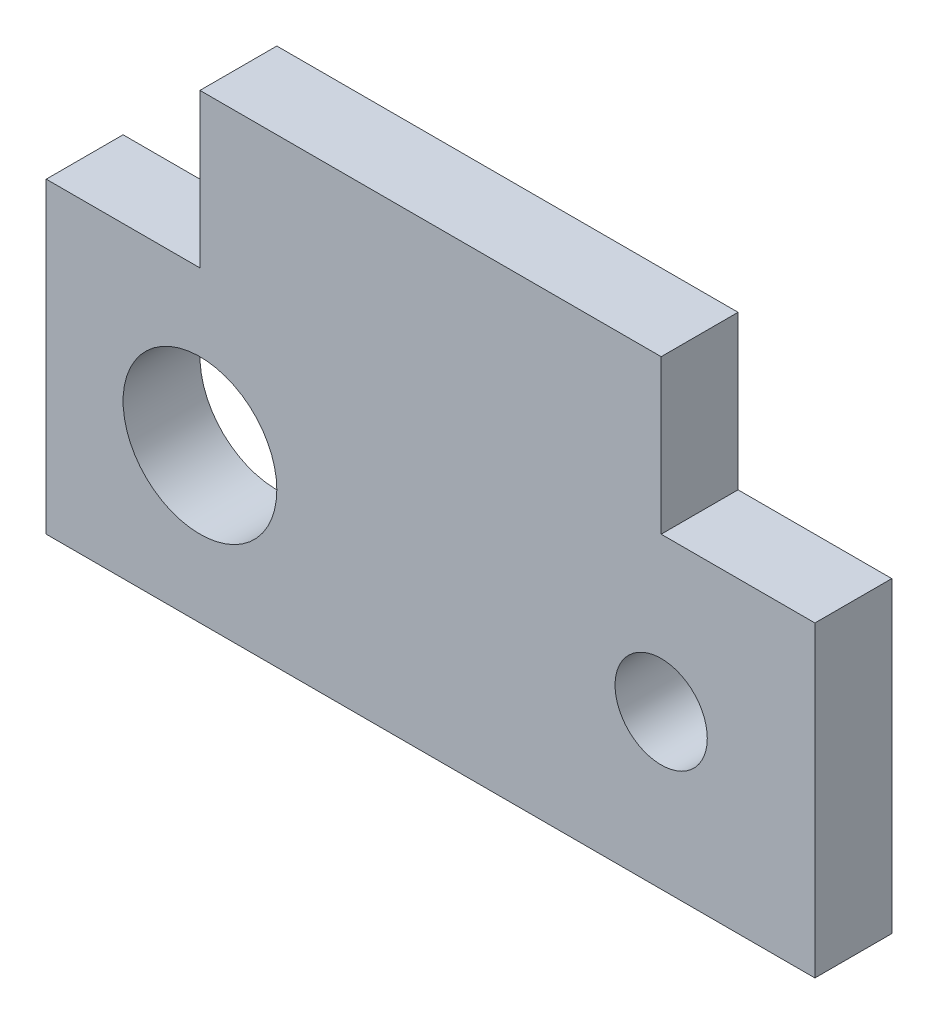
SolidWorks part; units mm, degrees
ref_plane "Alzado" through (0, 0, 0) normal (0, 0, 1) x (1, 0, 0)
ref_plane "Planta" through (0, 0, 0) normal (0, 1, 0) x (1, 0, 0)
ref_plane "Vista lateral" through (0, 0, 0) normal (1, 0, 0) x (0, 0, -1)
sketch "Croquis1" plane through (0, 0, 0) normal (0, 0, 1) x (1, 0, 0)
  line L0 (40, 20) -> (50, 20)
  line L1 (0, 0) -> (50, 0)
  line L2 (0, 0) -> (0, 20)
  line L3 (0, 20) -> (10, 20)
  line L4 (50, 0) -> (50, 20)
  line L6 (40, 20) -> (40, 30)
  line L7 (40, 30) -> (10, 30)
  line L8 (10, 20) -> (10, 30)
  circle A0 centre (10, 10) radius 5
  circle A1 centre (40, 10) radius 3
  point P13 (0, 0)
  point P14 (0, 0)
  point P15 (0, 0)
  dimension "D2" = 10
  dimension "D3" = 6
  dimension "D1" = 20
  dimension "D4" = 10
  dimension "D5" = 10
  dimension "D6" = 50
  dimension "D7" = 10
  dimension "D8" = 10
  dimension "D9" = 30
extrude "Saliente-Extruir1" add sketch "Croquis1" along normal blind 5
